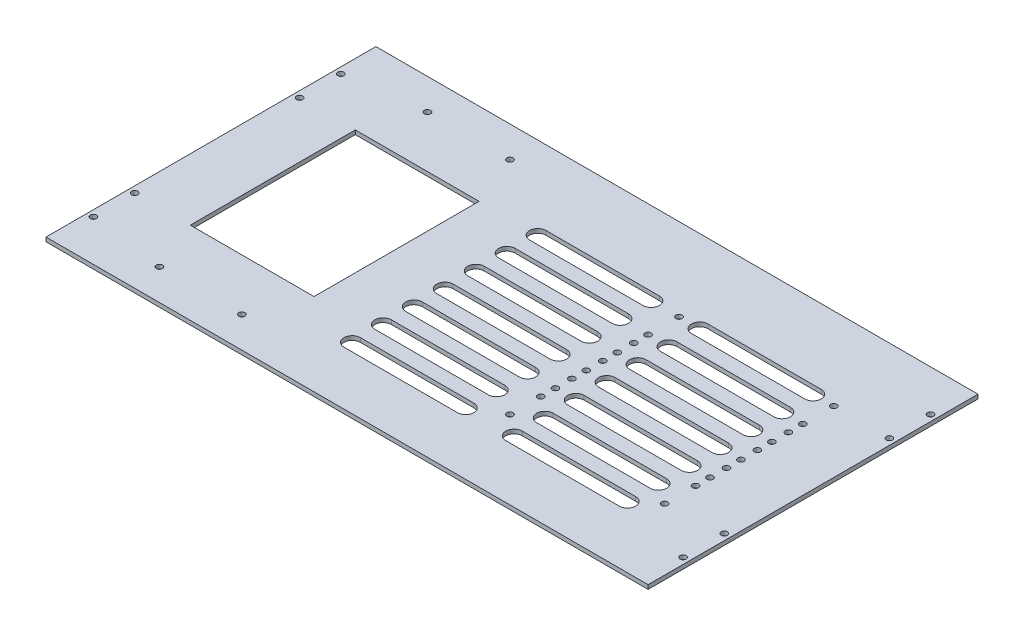
SolidWorks part; units mm, degrees
material "Thornel Mat VMA"
ref_plane "前视基准面" through (0, 0, 0) normal (0, 0, 1) x (1, 0, 0)
ref_plane "上视基准面" through (0, 0, 0) normal (0, 1, 0) x (1, 0, 0)
ref_plane "右视基准面" through (0, 0, 0) normal (1, 0, 0) x (0, 0, -1)
sketch "草图1" plane through (0, 0, 0) normal (0, 1, 0) x (1, 0, 0)
  line L0 (3, 40) -> (3, 20) construction
  line L1 (0, 0) -> (292, 0)
  line L2 (0, 0) -> (0, 160)
  line L3 (0, 160) -> (292, 160)
  line L4 (292, 0) -> (292, 160)
  line L5 (3, 140) -> (3, 120) construction
  line L6 (146, 160) -> (146, 0) construction
  line L7 (289, 40) -> (289, 20) construction
  line L8 (289, 140) -> (289, 120) construction
  line L9 (0, 80) -> (30, 80) construction
  line L10 (30, 120) -> (90, 120)
  line L11 (30, 120) -> (30, 40)
  line L12 (30, 40) -> (90, 40)
  line L13 (90, 120) -> (90, 40)
  line L14 (197, 120) -> (252, 120) construction
  line L15 (187, 120) -> (262, 120) construction
  line L16 (187, 120) -> (187, 98) construction
  line L17 (187, 98) -> (262, 98) construction
  line L18 (262, 120) -> (262, 98) construction
  line L19 (40, 145) -> (80, 145) construction
  line L20 (40, 145) -> (40, 15) construction
  line L21 (40, 15) -> (80, 15) construction
  line L22 (80, 145) -> (80, 15) construction
  line L27 (197, 124) -> (252, 124)
  line L28 (197, 116) -> (252, 116)
  line L29 (197, 101) -> (252, 101)
  line L30 (197, 109) -> (252, 109)
  line L31 (197, 105) -> (252, 105) construction
  line L32 (197, 86) -> (252, 86)
  line L33 (197, 94) -> (252, 94)
  line L34 (197, 90) -> (252, 90) construction
  line L35 (197, 71) -> (252, 71)
  line L36 (197, 79) -> (252, 79)
  line L37 (197, 75) -> (252, 75) construction
  line L38 (197, 56) -> (252, 56)
  line L39 (197, 64) -> (252, 64)
  line L40 (197, 60) -> (252, 60) construction
  line L41 (197, 45) -> (252, 45) construction
  line L42 (197, 49) -> (252, 49)
  line L43 (197, 41) -> (252, 41)
  line L44 (197, 30) -> (252, 30) construction
  line L45 (197, 34) -> (252, 34)
  line L46 (197, 26) -> (252, 26)
  line L47 (118.5, 116) -> (173.5, 116)
  line L48 (118.5, 124) -> (173.5, 124)
  line L49 (118.5, 109) -> (173.5, 109)
  line L50 (118.5, 101) -> (173.5, 101)
  line L51 (118.5, 94) -> (173.5, 94)
  line L52 (118.5, 86) -> (173.5, 86)
  line L53 (118.5, 79) -> (173.5, 79)
  line L54 (118.5, 71) -> (173.5, 71)
  line L55 (118.5, 64) -> (173.5, 64)
  line L56 (118.5, 56) -> (173.5, 56)
  line L57 (118.5, 49) -> (173.5, 49)
  line L58 (118.5, 41) -> (173.5, 41)
  line L59 (118.5, 34) -> (173.5, 34)
  line L60 (118.5, 26) -> (173.5, 26)
  line L61 (118.5, 120) -> (173.5, 120) construction
  line L62 (118.5, 105) -> (173.5, 105) construction
  line L63 (118.5, 90) -> (173.5, 90) construction
  line L64 (118.5, 75) -> (173.5, 75) construction
  line L65 (118.5, 60) -> (173.5, 60) construction
  line L66 (118.5, 45) -> (173.5, 45) construction
  line L67 (118.5, 30) -> (173.5, 30) construction
  circle A0 centre (3, 140) radius 1.5
  circle A1 centre (3, 120) radius 1.5
  circle A2 centre (3, 40) radius 1.5
  circle A3 centre (3, 20) radius 1.5
  circle A4 centre (289, 20) radius 1.5
  circle A5 centre (289, 40) radius 1.5
  circle A6 centre (289, 120) radius 1.5
  circle A7 centre (289, 140) radius 1.5
  circle A8 centre (187, 120) radius 1.5
  circle A9 centre (262, 120) radius 1.5
  circle A10 centre (262, 98) radius 1.5
  circle A11 centre (187, 98) radius 1.5
  circle A12 centre (187, 105) radius 1.5
  circle A13 centre (262, 105) radius 1.5
  circle A14 centre (187, 83) radius 1.5
  circle A15 centre (262, 83) radius 1.5
  circle A16 centre (187, 90) radius 1.5
  circle A17 centre (262, 90) radius 1.5
  circle A18 centre (187, 68) radius 1.5
  circle A19 centre (262, 68) radius 1.5
  circle A20 centre (187, 75) radius 1.5
  circle A21 centre (262, 75) radius 1.5
  circle A22 centre (187, 53) radius 1.5
  circle A23 centre (262, 53) radius 1.5
  circle A24 centre (187, 60) radius 1.5
  circle A25 centre (262, 60) radius 1.5
  circle A26 centre (187, 38) radius 1.5
  circle A27 centre (262, 38) radius 1.5
  circle A28 centre (40, 145) radius 1.5
  circle A29 centre (80, 145) radius 1.5
  circle A30 centre (40, 15) radius 1.5
  circle A31 centre (80, 15) radius 1.5
  arc A32 (197, 124) -> (197, 116) centre (197, 120) ccw
  arc A33 (252, 116) -> (252, 124) centre (252, 120) ccw
  arc A34 (197, 109) -> (197, 101) centre (197, 105) ccw
  arc A35 (252, 101) -> (252, 109) centre (252, 105) ccw
  arc A36 (197, 94) -> (197, 86) centre (197, 90) ccw
  arc A37 (252, 86) -> (252, 94) centre (252, 90) ccw
  arc A38 (197, 79) -> (197, 71) centre (197, 75) ccw
  arc A39 (252, 71) -> (252, 79) centre (252, 75) ccw
  arc A40 (197, 64) -> (197, 56) centre (197, 60) ccw
  arc A41 (252, 56) -> (252, 64) centre (252, 60) ccw
  arc A42 (197, 49) -> (197, 41) centre (197, 45) ccw
  arc A43 (252, 41) -> (252, 49) centre (252, 45) ccw
  arc A44 (197, 34) -> (197, 26) centre (197, 30) ccw
  arc A45 (252, 26) -> (252, 34) centre (252, 30) ccw
  arc A46 (118.5, 124) -> (118.5, 116) centre (118.5, 120) ccw
  arc A47 (173.5, 116) -> (173.5, 124) centre (173.5, 120) ccw
  arc A48 (173.5, 101) -> (173.5, 109) centre (173.5, 105) ccw
  arc A49 (118.5, 109) -> (118.5, 101) centre (118.5, 105) ccw
  arc A50 (173.5, 86) -> (173.5, 94) centre (173.5, 90) ccw
  arc A51 (118.5, 94) -> (118.5, 86) centre (118.5, 90) ccw
  arc A52 (173.5, 71) -> (173.5, 79) centre (173.5, 75) ccw
  arc A53 (118.5, 79) -> (118.5, 71) centre (118.5, 75) ccw
  arc A54 (173.5, 56) -> (173.5, 64) centre (173.5, 60) ccw
  arc A55 (118.5, 64) -> (118.5, 56) centre (118.5, 60) ccw
  arc A56 (173.5, 41) -> (173.5, 49) centre (173.5, 45) ccw
  arc A57 (118.5, 49) -> (118.5, 41) centre (118.5, 45) ccw
  arc A58 (173.5, 26) -> (173.5, 34) centre (173.5, 30) ccw
  arc A59 (118.5, 34) -> (118.5, 26) centre (118.5, 30) ccw
  point P79 (224.5, 120)
  point P89 (224.5, 105)
  point P96 (224.5, 90)
  point P103 (224.5, 75)
  point P110 (224.5, 60)
  point P117 (224.5, 45)
  point P123 (224.5, 30)
  point P129 (146, 120)
  point P137 (146, 105)
  point P144 (146, 90)
  point P151 (146, 75)
  point P158 (146, 60)
  point P165 (146, 45)
  point P171 (146, 30)
  dimension "D3" = 20
  dimension "D5" = 3
  dimension "D7" = 20
  dimension "D14" = 3
  dimension "D23" = 3
  dimension "D26" = 4
  dimension "D1" = 292
  dimension "D2" = 160
  dimension "D4" = 3
  dimension "D6" = 20
  dimension "D8" = 20
  dimension "D9" = 80
  dimension "D10" = 60
  dimension "D11" = 30
  dimension "D12" = 22
  dimension "D13" = 75
  dimension "D15" = 40
  dimension "D16" = 30
  dimension "D18" = 15
  dimension "D19" = 15
  dimension "D20" = 15
  dimension "D21" = 10
  dimension "D22" = 10
  dimension "D24" = 10
  dimension "D25" = 10
  dimension "D28" = 15
  dimension "D17" = 5
  dimension "D27" = 3
  dimension "D29" = 2
extrude "凸台-拉伸1" add sketch "草图1" along normal blind 2
